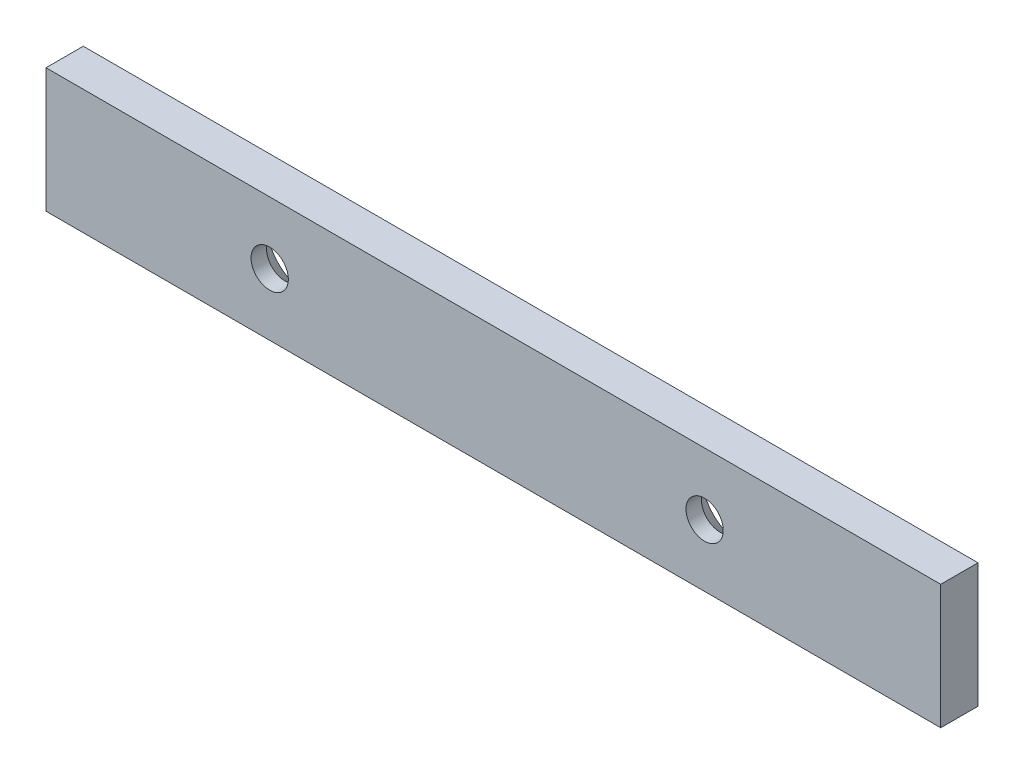
SolidWorks part; units mm, degrees
ref_plane "Front Plane" through (0, 0, 0) normal (0, 0, 1) x (1, 0, 0)
ref_plane "Top Plane" through (0, 0, 0) normal (0, 1, 0) x (1, 0, 0)
ref_plane "Right Plane" through (0, 0, 0) normal (1, 0, 0) x (0, 0, -1)
sketch "Sketch1" plane through (0, 0, 0) normal (0, 0, 1) x (1, 0, 0)
  line L1 (-55.6642, 14.316) -> (88.3358, 14.316)
  line L2 (-55.6642, 14.316) -> (-55.6642, -5.684)
  line L3 (-55.6642, -5.684) -> (88.3358, -5.684)
  line L4 (88.3358, 14.316) -> (88.3358, -5.684)
  dimension "D1" = 20
  dimension "D2" = 144
extrude "Boss-Extrude1" add sketch "Sketch1" along normal blind 6
sketch "Sketch2" plane through (0, 0, 0) normal (0, 0, 1) x (1, 0, 0)
  line L0 (88.3358, -5.684) -> (88.3358, 14.316) construction
  point P0 (50.3358, 4.316)
  point P1 (-19.6642, 4.316)
  point P2 (88.3358, 4.316)
  dimension "D1" = 38
  dimension "D2" = 70
hole_wizard "CSK for M6 Countersunk Flat Head Screw1" positions "Sketch5" profile "Sketch4" countersink size "M6" standard "ISO"
sketch "Sketch5" plane through (0, 0, 0) normal (0, 0, -1) x (-1, 0, 0)
  point P0 (-50.3358, 4.316)
  point P3 (19.6642, 4.316)
sketch "Sketch4" plane through (50.3358, 4.316, 0) normal (1, 0, 0) x (0, 1, 0)
  line L0 (0, 0) -> (0, 19.3026)
  line L1 (0, 19.3026) -> (3, 17.5)
  line L2 (3, 17.5) -> (3, 3.5)
  line L3 (3, 3.5) -> (6.5, 0)
  line L5 (6.5, 0) -> (0, 0)
  line L6 (-3, 3.5) -> (-6.5, 0) construction
  line L10 (0, 19.3026) -> (-3, 17.5) construction
  line L11 (0, -6.35) -> (0, 107.95) construction
  dimension "Hole Dia." = 6
  dimension "Hole Depth" = 17.5
  dimension "Near C'Sink Dia." = 13
  dimension "Near C'Sink Angle" = 90
  dimension "Drill Angle" = 118
